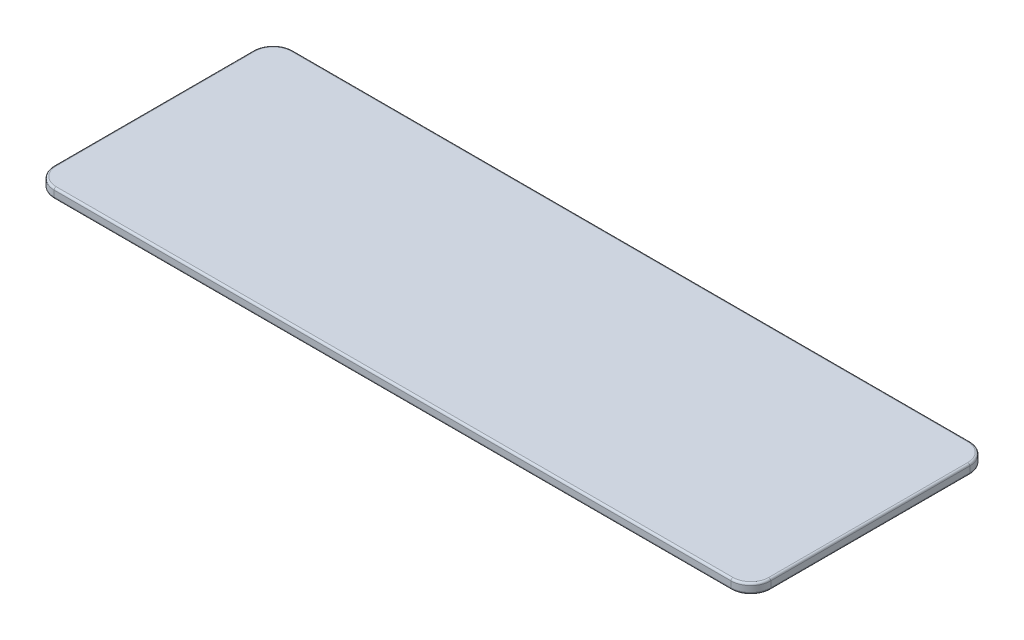
SolidWorks part; units mm, degrees
material "ABS PC"
ref_plane "Front" through (0, 0, 0) normal (0, 0, 1) x (1, 0, 0)
ref_plane "Top" through (0, 0, 0) normal (0, 1, 0) x (1, 0, 0)
ref_plane "Right" through (0, 0, 0) normal (1, 0, 0) x (0, 0, -1)
sketch "Sketch1" plane through (0, 0, 0) normal (0, 1, 0) x (1, 0, 0)
  line L1 (-228.6, 76.2) -> (228.6, 76.2)
  line L2 (-228.6, 76.2) -> (-228.6, -76.2)
  line L3 (-228.6, -76.2) -> (228.6, -76.2)
  line L4 (228.6, 76.2) -> (228.6, -76.2)
  point P4 (-228.6, 0)
  point P6 (0, 76.2)
  dimension "D1" = 457.2
  dimension "D2" = 152.4
extrude "Boss-Extrude1" add sketch "Sketch1" along normal blind 6.35
fillet "Fillet2" radius 12.7 4 edges at (228.6, 3.175, 76.2) (228.6, 3.175, -76.2) (-228.6, 3.175, -76.2) (-228.6, 3.175, 76.2)
fillet "Fillet3" radius 1.27 16 edges at (-224.8803, 6.35, 72.4803) (-228.6, 6.35, 0) (-224.8803, 6.35, -72.4803) (0, 6.35, -76.2) (224.8803, 6.35, -72.4803) (228.6, 6.35, 0) (224.8803, 6.35, 72.4803) (0, 6.35, 76.2) (224.8803, 0, -72.4803) (0, 0, -76.2) (-224.8803, 0, -72.4803) (-228.6, 0, 0) (-224.8803, 0, 72.4803) (0, 0, 76.2) (224.8803, 0, 72.4803) (228.6, 0, 0)
